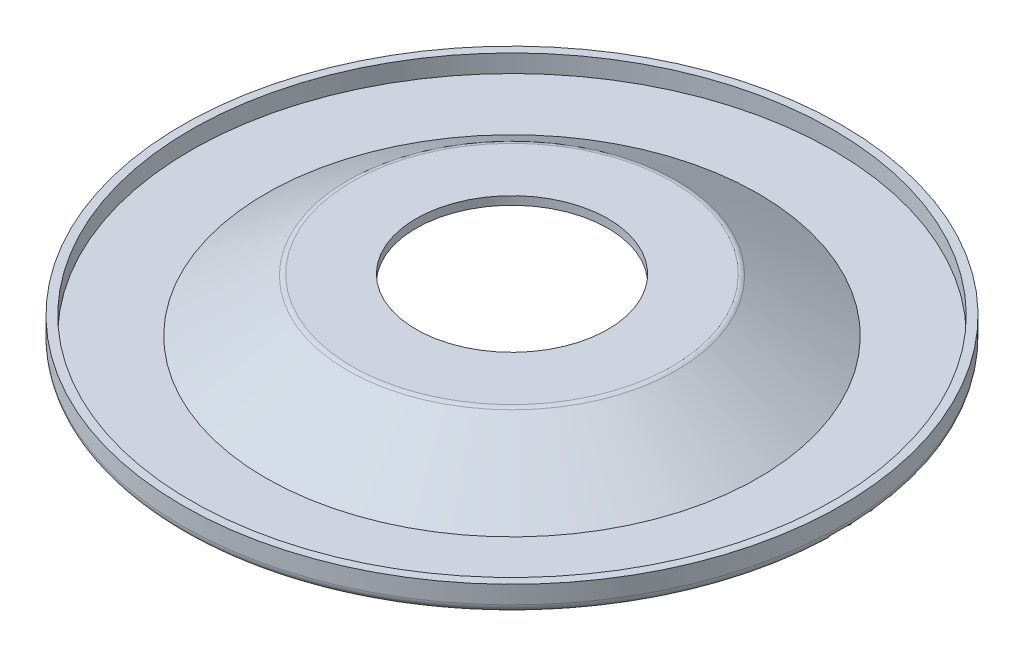
SolidWorks part; units mm, degrees
material "AISI 1020"
ref_plane "Alzado" through (0, 0, 0) normal (0, 0, 1) x (1, 0, 0)
ref_plane "Planta" through (0, 0, 0) normal (0, 1, 0) x (1, 0, 0)
ref_plane "Vista lateral" through (0, 0, 0) normal (1, 0, 0) x (0, 0, -1)
sketch "Croquis1" plane through (0, 0, 0) normal (0, 0, 1) x (1, 0, 0)
  line L8 (-8.065, 0) -> (-13.45, 0)
  line L10 (-20.7, -4.5) -> (-27, -4.5)
  line L11 (-27, -4.5) -> (-27, -3)
  line L12 (-8.065, -0.7) -> (-13.45, -0.7)
  line L14 (-20.7, -5.2) -> (-27, -5.2)
  line L15 (-27.7, -4.5) -> (-27.7, -3)
  line L16 (-27, -3) -> (-27.7, -3)
  line L17 (-8.065, -0.7) -> (-8.065, 0)
  line L18 (0, 0) -> (0, 119.1499) construction
  line L19 (-27.7, -3) -> (-27.7, 4.547) construction
  line L20 (-13.8268, -0.1101) -> (-20.7, -4.5)
  line L21 (-13.45, -0.7) -> (-20.3232, -5.0899)
  arc A0 (-13.45, 0) -> (-13.8268, -0.1101) centre (-13.45, -0.7) ccw
  arc A1 (-20.3232, -5.0899) -> (-20.7, -5.2) centre (-20.7, -4.5) cw
  arc A2 (-27, -5.2) -> (-27.7, -4.5) centre (-27, -4.5) cw
  dimension "D13" = 0.7
  dimension "D14" = 0.7
  dimension "D15" = 0.7
  dimension "D1" = 0.7
  dimension "D2" = 27.7
  dimension "D3" = 16.13
  dimension "D4" = 1.5
  dimension "D5" = 0.7
  dimension "D6" = 4.5
  dimension "D7" = 0.7
  dimension "D8" = 0.7
  dimension "D9" = 6.3
  dimension "D12" = 26.9
revolve "Revolución1" add sketch "Croquis1" angle 360 about L18
